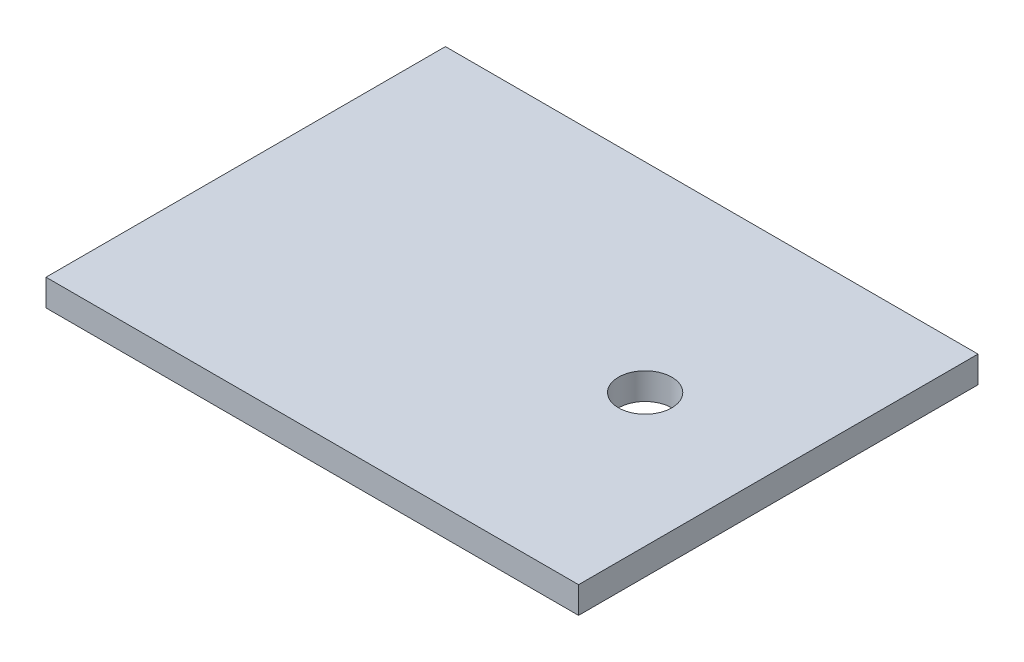
SolidWorks part; units mm, degrees
ref_plane "Front Plane" through (0, 0, 0) normal (0, 0, 1) x (1, 0, 0)
ref_plane "Top Plane" through (0, 0, 0) normal (0, 1, 0) x (1, 0, 0)
ref_plane "Right Plane" through (0, 0, 0) normal (1, 0, 0) x (0, 0, -1)
sketch "Sketch1" plane through (0, 0, 0) normal (0, 1, 0) x (1, 0, 0)
  line L1 (-100, 75) -> (100, 75)
  line L2 (-100, 75) -> (-100, -75)
  line L3 (-100, -75) -> (100, -75)
  line L4 (100, 75) -> (100, -75)
  line L5 (-100, 75) -> (100, -75) construction
  line L6 (-100, -75) -> (100, 75) construction
  point P0 (0, 0)
  dimension "D1" = 150
  dimension "D2" = 200
extrude "Boss-Extrude1" add sketch "Sketch1" along normal blind 10
sketch "Sketch2" plane through (0, 10, 0) normal (0, 1, 0) x (1, 0, 0)
  line L0 (100, 75) -> (-100, 75) construction
  line L1 (100, -75) -> (100, 75) construction
  line L2 (-100, -75) -> (100, -75) construction
  circle A0 centre (50, 0) radius 10
  point P4 (0, 0)
  dimension "D1" = 20
  dimension "D2" = 75
  dimension "D3" = 50
  dimension "D4" = 75
extrude "Cut-Extrude1" cut sketch "Sketch2" against normal blind 20
